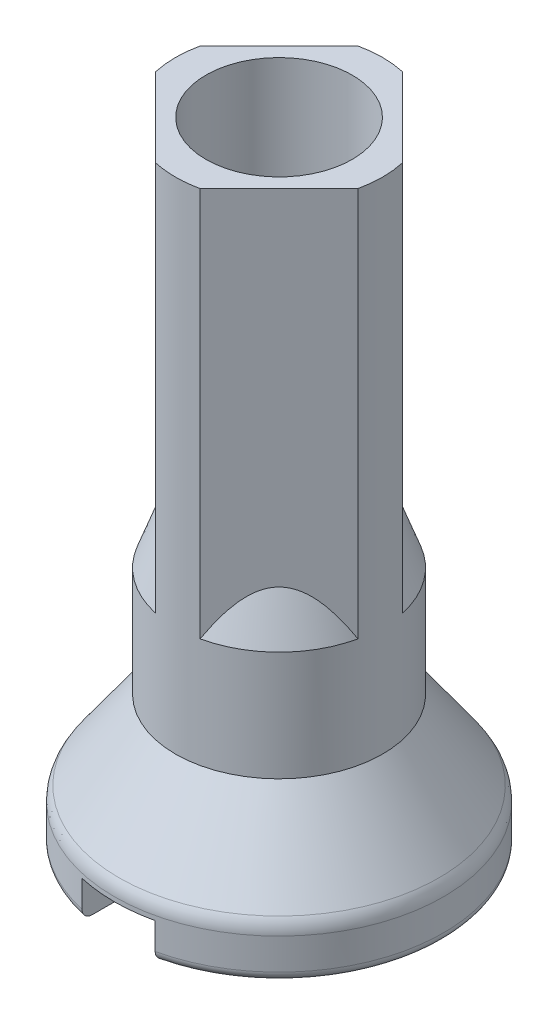
SolidWorks part; units mm, degrees
material "Alloy Steel"
ref_plane "Front Plane" through (0, 0, 0) normal (0, 0, 1) x (1, 0, 0)
ref_plane "Top Plane" through (0, 0, 0) normal (0, 1, 0) x (1, 0, 0)
ref_plane "Right Plane" through (0, 0, 0) normal (1, 0, 0) x (0, 0, -1)
sketch "Sketch1" plane through (0, 0, 0) normal (0, 0, 1) x (1, 0, 0)
  line L0 (0, 13) -> (0, 0) construction
  line L1 (1, 0) -> (3.175, 0)
  line L2 (3.375, 0.2) -> (3.375, 0.8398)
  line L3 (2.125, 2.75) -> (2.125, 9.05)
  line L4 (2.125, 2.75) -> (3.2819, 1.1304)
  line L5 (2.125, 2.75) -> (0, 2.75) construction
  line L6 (2.125, 13) -> (2.125, 9.05)
  line L7 (0, 13) -> (1, 13) construction
  line L8 (1, 13) -> (2.125, 13)
  line L9 (1, 0) -> (1, 13)
  line L10 (2.125, 9.05) -> (1, 9.05) construction
  arc A0 (3.375, 0.2) -> (3.175, 0) centre (3.175, 0.2) cw
  arc A1 (3.375, 0.8398) -> (3.2819, 1.1304) centre (2.875, 0.8398) ccw
  dimension "D3" = 0.2
  dimension "D4" = 0.5
  dimension "D1" = 6.3
  dimension "D2" = 3.95
  dimension "D5" = 1
revolve "Revolve1" add sketch "Sketch1" angle 360 about L0
sketch "Sketch2" plane through (0, 13, 0) normal (0, 1, 0) x (1, 0, 0)
  line L0 (0, 2.5314) -> (-2.5314, 0)
  line L1 (-2.5314, 0) -> (0, -2.5314)
  line L2 (0, -2.5314) -> (2.5314, 0)
  line L3 (2.5314, 0) -> (0, 2.5314)
  circle A0 centre (0, 0) radius 1.79 construction
  dimension "D1" = 3.58
  dimension "D2" = 3.58
extrude "Cut-Extrude1" cut sketch "Sketch2" against normal blind 8 flip side to cut
sketch "Sketch3" plane through (0, 5, 0) normal (0, 1, 0) x (1, 0, 0)
  circle A0 centre (0, 0) radius 2.125 construction
  circle A1 centre (0, 0) radius 2.125
extrude "Boss-Extrude1" add sketch "Sketch3" along normal blind 8 draft 20
sketch "Sketch4" plane through (0, 13, 0) normal (0, 1, 0) x (1, 0, 0)
  circle A0 centre (0, 0) radius 1.5
extrude "Cut-Extrude2" cut sketch "Sketch4" against normal blind 8
sketch "Sketch5" plane through (0, 0, 0) normal (0, -1, 0) x (1, 0, 0)
  line L0 (0, 3.375) -> (0, -3.375) construction
  line L1 (0.75, 3.375) -> (0.75, -3.375)
  line L2 (-0.75, 3.375) -> (-0.75, -3.375)
  line L3 (-0.75, 3.375) -> (0.75, 3.375)
  line L4 (-0.75, -3.375) -> (0.75, -3.375)
extrude "Cut-Extrude3" cut sketch "Sketch5" against normal blind 0.75
